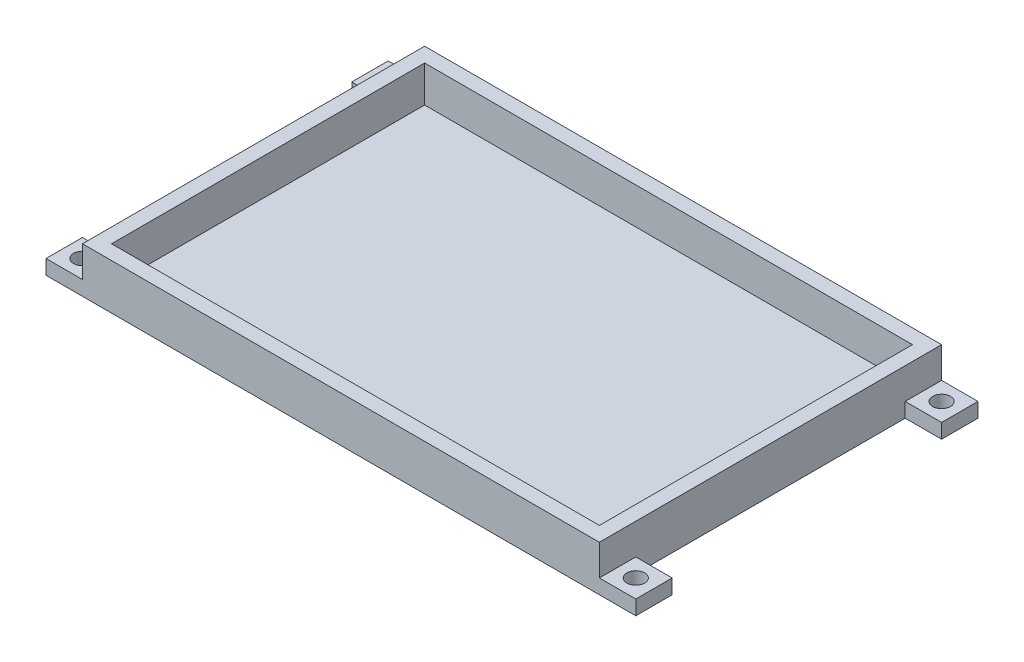
SolidWorks part; units mm, degrees
ref_plane "Front Plane" through (0, 0, 0) normal (0, 0, 1) x (1, 0, 0)
ref_plane "Top Plane" through (0, 0, 0) normal (0, 1, 0) x (1, 0, 0)
ref_plane "Right Plane" through (0, 0, 0) normal (1, 0, 0) x (0, 0, -1)
sketch "Sketch1" plane through (0, 0, 0) normal (0, 1, 0) x (1, 0, 0)
  line L0 (-2.54, 57.15) -> (87.63, 57.15)
  line L1 (0, 0) -> (85.09, 0)
  line L2 (0, 0) -> (0, 54.61)
  line L3 (0, 54.61) -> (85.09, 54.61)
  line L4 (85.09, 0) -> (85.09, 54.61)
  line L5 (87.63, 57.15) -> (87.63, -2.54)
  line L6 (87.63, -2.54) -> (-2.54, -2.54)
  line L7 (-2.54, -2.54) -> (-2.54, 57.15)
  dimension "D1" = 85.09
  dimension "D2" = 54.61
  dimension "D3" = 2.54
  dimension "D4" = 2.54
  dimension "D5" = 2.54
  dimension "D6" = 2.54
extrude "Boss-Extrude1" add sketch "Sketch1" along normal blind 6.35
sketch "Sketch2" plane through (0, 0, 0) normal (0, -1, 0) x (1, 0, 0)
  line L1 (87.63, -57.15) -> (-2.54, -57.15)
  line L2 (87.63, -57.15) -> (87.63, 2.54)
  line L3 (87.63, 2.54) -> (-2.54, 2.54)
  line L4 (-2.54, -57.15) -> (-2.54, 2.54)
extrude "Boss-Extrude2" add sketch "Sketch2" along normal blind 1.5875
sketch "Sketch3" plane through (0, -1.5875, 0) normal (0, -1, 0) x (1, 0, 0)
  line L0 (87.63, -57.15) -> (87.63, 2.54) construction
  line L1 (87.63, -50.8) -> (93.98, -50.8)
  line L2 (87.63, -50.8) -> (87.63, -57.15)
  line L3 (87.63, -57.15) -> (93.98, -57.15)
  line L4 (93.98, -50.8) -> (93.98, -57.15)
  line L5 (-2.54, -57.15) -> (87.63, -57.15) construction
  line L6 (-2.54, -27.305) -> (87.63, -27.305) construction
  line L7 (-2.54, 2.54) -> (-2.54, -57.15) construction
  line L8 (42.545, 2.54) -> (42.545, -57.15) construction
  line L9 (87.63, 2.54) -> (-2.54, 2.54) construction
  line L10 (-8.89, -50.8) -> (-8.89, -57.15)
  line L11 (-2.54, -57.15) -> (-8.89, -57.15)
  line L12 (-2.54, -50.8) -> (-2.54, -57.15)
  line L13 (-2.54, -50.8) -> (-8.89, -50.8)
  line L14 (87.63, -50.8) -> (93.98, -50.8)
  line L15 (87.63, -50.8) -> (87.63, -57.15)
  line L16 (87.63, -57.15) -> (93.98, -57.15)
  line L17 (93.98, -50.8) -> (93.98, -57.15)
  line L18 (-8.89, -50.8) -> (-8.89, -57.15)
  line L19 (-2.54, -57.15) -> (-8.89, -57.15)
  line L20 (-2.54, -50.8) -> (-2.54, -57.15)
  line L21 (-2.54, -50.8) -> (-8.89, -50.8)
  line L22 (-2.54, -3.81) -> (-8.89, -3.81)
  line L23 (-2.54, -3.81) -> (-2.54, 2.54)
  line L24 (-2.54, 2.54) -> (-8.89, 2.54)
  line L25 (-8.89, -3.81) -> (-8.89, 2.54)
  line L26 (93.98, -3.81) -> (93.98, 2.54)
  line L27 (87.63, 2.54) -> (93.98, 2.54)
  line L28 (87.63, -3.81) -> (87.63, 2.54)
  line L29 (87.63, -3.81) -> (93.98, -3.81)
  line L30 (-2.54, -3.81) -> (-8.89, -3.81)
  line L31 (-2.54, -3.81) -> (-2.54, 2.54)
  line L32 (-2.54, 2.54) -> (-8.89, 2.54)
  line L33 (-8.89, -3.81) -> (-8.89, 2.54)
  line L34 (93.98, -3.81) -> (93.98, 2.54)
  line L35 (87.63, 2.54) -> (93.98, 2.54)
  line L36 (87.63, -3.81) -> (87.63, 2.54)
  line L37 (87.63, -3.81) -> (93.98, -3.81)
  circle A0 centre (90.805, -53.975) radius 1.55
  circle A1 centre (-5.715, -53.975) radius 1.55
  circle A2 centre (90.805, -53.975) radius 1.55
  circle A3 centre (-5.715, -53.975) radius 1.55
  circle A4 centre (-5.715, -0.635) radius 1.55
  circle A5 centre (90.805, -0.635) radius 1.55
  circle A6 centre (-5.715, -0.635) radius 1.55
  circle A7 centre (90.805, -0.635) radius 1.55
  line M6 (87.63, -57.15) -> (87.63, 2.54)
  line M8 (-2.54, 2.54) -> (-2.54, -57.15)
  dimension "D4" = 3.1
  dimension "D1" = 6.35
  dimension "D2" = 6.35
  dimension "D3" = 0
  dimension "D5" = 3.175
  dimension "D6" = 3.175
extrude "Boss-Extrude3" add sketch "Sketch3" against normal blind 2.54 contours L29 L26 L27 A5 M6 | L25 L22 L24 A4 M8 | L13 L10 L11 A1 M8 | L4 L1 L3 A0 M6
